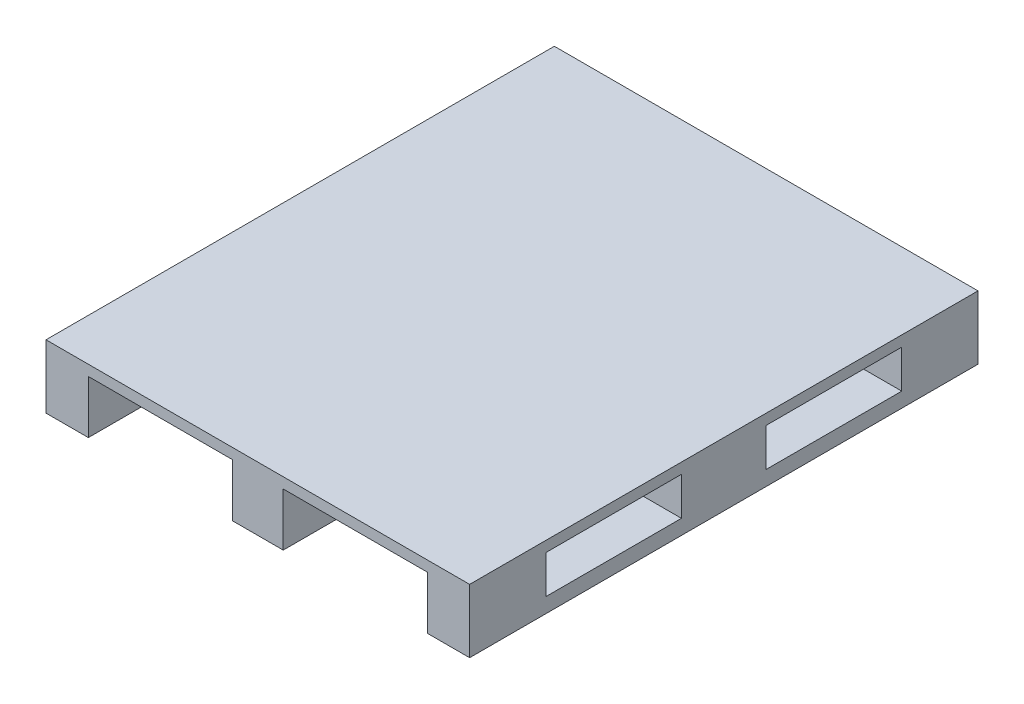
SolidWorks part; units mm, degrees
ref_plane "Front" through (0, 0, 0) normal (0, 0, 1) x (1, 0, 0)
ref_plane "Top" through (0, 0, 0) normal (0, 1, 0) x (1, 0, 0)
ref_plane "Right" through (0, 0, 0) normal (1, 0, 0) x (0, 0, -1)
sketch "草图1" plane through (0, 0, 0) normal (0, 1, 0) x (1, 0, 0)
  line L1 (500, -600) -> (-500, -600)
  line L2 (500, -600) -> (500, 600)
  line L3 (500, 600) -> (-500, 600)
  line L4 (-500, -600) -> (-500, 600)
  line L5 (500, -600) -> (-500, 600) construction
  line L6 (500, 600) -> (-500, -600) construction
  point P0 (0, 0)
  dimension "D1" = 1000
  dimension "D2" = 1200
extrude "凸台-拉伸1" add sketch "草图1" along normal mid plane 150
sketch "草图2" plane through (0, 0, 600) normal (0, 0, 1) x (1, 0, 0)
  line L4 (0, 0) -> (0, -157.2713) construction
  line L10 (-500, -75) -> (500, -75) construction
  line L11 (-60, 50) -> (-400, 50)
  line L12 (-60, 50) -> (-60, -75)
  line L13 (-60, -75) -> (-400, -75)
  line L14 (-400, 50) -> (-400, -75)
  line L15 (-60, 50) -> (-400, -75) construction
  line L16 (-60, -75) -> (-400, 50) construction
  line L17 (60, -75) -> (400, -75)
  line L18 (400, 50) -> (400, -75)
  line L19 (60, 50) -> (400, 50)
  line L20 (60, 50) -> (60, -75)
  line L21 (60, -75) -> (400, 50) construction
  line L22 (60, 50) -> (400, -75) construction
  line L23 (-500, 75) -> (-500, -75) construction
  line L25 (-500, 75) -> (500, 75) construction
  point P0 (-230, -12.5)
  point P14 (230, -12.5)
  dimension "D1" = 100
  dimension "D2" = 120
  dimension "D3" = 25
extrude "切除-拉伸1" cut sketch "草图2" against normal up to next
sketch "草图3" plane through (-500, 0, 0) normal (-1, 0, 0) x (0, 0, 1)
  line L0 (0, 0) -> (0, -120.891) construction
  line L1 (100, 50) -> (420, 50)
  line L2 (-100, -40) -> (-420, -40)
  line L3 (-100, -40) -> (-100, 50)
  line L4 (-100, 50) -> (-420, 50)
  line L5 (-420, -40) -> (-420, 50)
  line L6 (-100, -40) -> (-420, 50) construction
  line L7 (-100, 50) -> (-420, -40) construction
  line L8 (420, -40) -> (420, 50)
  line L9 (100, -40) -> (420, -40)
  line L10 (100, -40) -> (100, 50)
  line L11 (100, 50) -> (420, -40) construction
  line L12 (100, -40) -> (420, 50) construction
  line L13 (-600, 75) -> (600, 75) construction
  line L14 (-600, -75) -> (600, -75) construction
  line L15 (-600, 75) -> (-600, -75) construction
  point P3 (-260, 5)
  point P12 (260, 5)
  dimension "D1" = 25
  dimension "D2" = 35
  dimension "D3" = 180
  dimension "D4" = 200
extrude "切除-拉伸2" cut sketch "草图3" against normal through all
